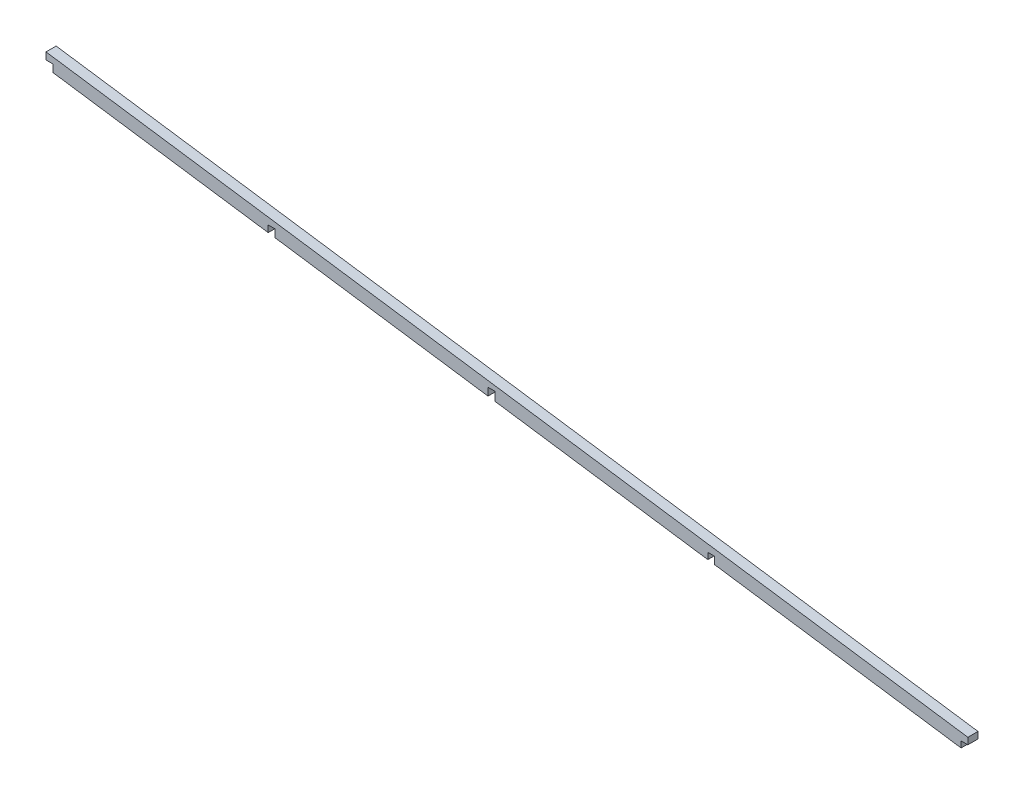
SolidWorks part; units mm, degrees
ref_plane "前视基准面" through (0, 0, 0) normal (0, 0, 1) x (1, 0, 0)
ref_plane "上视基准面" through (0, 0, 0) normal (0, 1, 0) x (1, 0, 0)
ref_plane "右视基准面" through (0, 0, 0) normal (1, 0, 0) x (0, 0, -1)
sketch "Model" plane through (0, 0, 0) normal (0, 0, 1) x (1, 0, 0)
  line L0 (23.0418, 10.8575) -> (86.7418, 1.6783)
  line L1 (88.7418, 1.3902) -> (151.7418, -7.6868)
  line L2 (153.7418, -7.9749) -> (216.7418, -17.0521)
  line L3 (218.7418, -17.3403) -> (281.7417, -26.4174)
  line L4 (21.0418, 15.1212) -> (293.6382, -24.1013)
  line L5 (216.7418, -17.0521) -> (216.7418, -15.1873)
  line L6 (216.7418, -15.1873) -> (218.7418, -15.1873)
  line L7 (218.7418, -15.1873) -> (218.7418, -17.3403)
  line L8 (151.7418, -7.6868) -> (151.7418, -5.4153)
  line L9 (151.7418, -5.4153) -> (153.7418, -5.4153)
  line L10 (153.7418, -5.4153) -> (153.7418, -7.9749)
  line L11 (86.7418, 1.6783) -> (86.7418, 3.6527)
  line L12 (86.7418, 3.6527) -> (88.7418, 3.6527)
  line L13 (88.7418, 3.6527) -> (88.7418, 1.3902)
  line L14 (23.0418, 10.8575) -> (23.0418, 13.0525)
  line L15 (23.0418, 13.0525) -> (21.0418, 13.0525)
  line L16 (21.0418, 13.0525) -> (21.0418, 15.1212)
  line L17 (291.6382, -27.8433) -> (291.6382, -26.0332)
  line L18 (291.6382, -26.0332) -> (293.6382, -26.0332)
  line L19 (293.6382, -24.1013) -> (293.6382, -26.0332)
  line L20 (281.7417, -26.4174) -> (291.6382, -27.8433)
extrude "凸台-拉伸2" add sketch "Model" along normal blind 3
